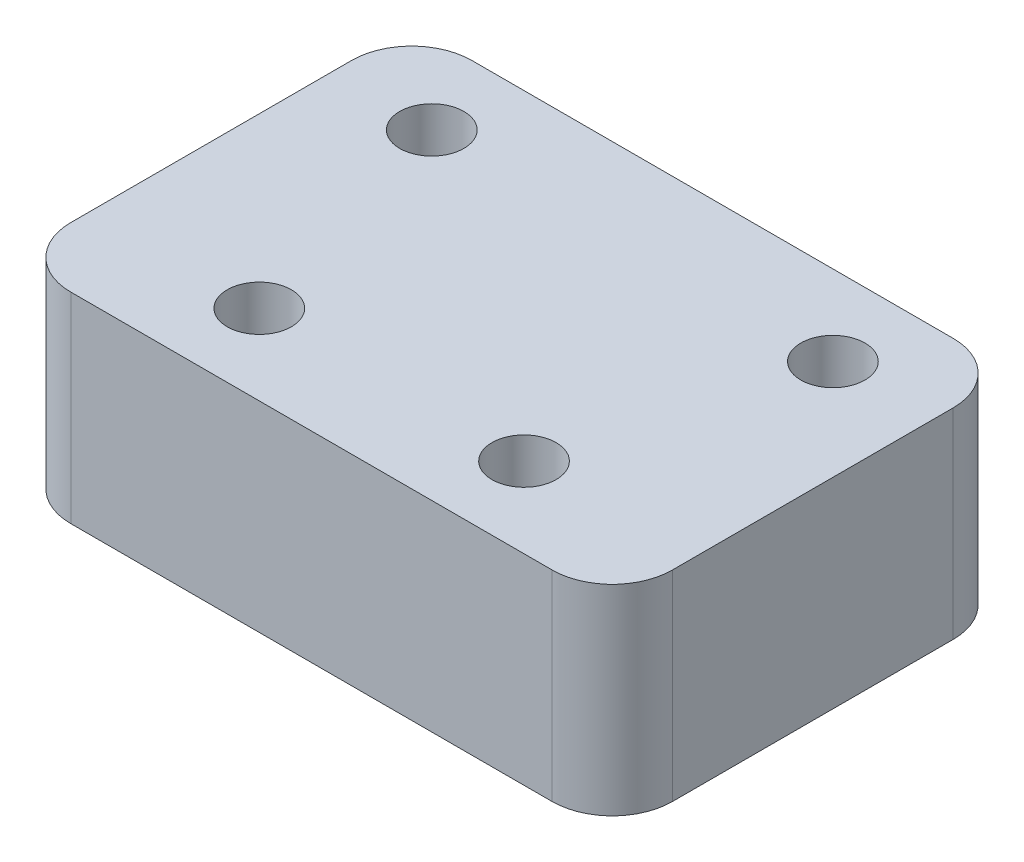
SolidWorks part; units mm, degrees
ref_plane "Front Plane" through (0, 0, 0) normal (0, 0, 1) x (1, 0, 0)
ref_plane "Top Plane" through (0, 0, 0) normal (0, 1, 0) x (1, 0, 0)
ref_plane "Right Plane" through (0, 0, 0) normal (1, 0, 0) x (0, 0, -1)
sketch "Sketch2" plane through (0, 0, 0) normal (0, 1, 0) x (1, 0, 0)
  line L0 (5, 16) -> (25, 16) construction
  line L1 (0, 0) -> (30, 0)
  line L2 (0, 0) -> (0, 20)
  line L3 (0, 20) -> (30, 20)
  line L4 (30, 0) -> (30, 20)
  line L5 (8.4, 4) -> (21.6, 4) construction
  circle A0 centre (5, 16) radius 1.6
  circle A1 centre (25, 16) radius 1.6
  circle A2 centre (8.4, 4) radius 1.6
  circle A3 centre (21.6, 4) radius 1.6
  dimension "D3" = 3.2
  dimension "D4" = 3.2
  dimension "D8" = 3.2
  dimension "D9" = 3.2
  dimension "D11" = 8.4
  dimension "D12" = 4
  dimension "D1" = 30
  dimension "D2" = 20
  dimension "D5" = 4
  dimension "D6" = 20
  dimension "D7" = 5
  dimension "D10" = 13.2
extrude "Boss-Extrude1" add sketch "Sketch2" along normal blind 10
fillet "Fillet1" radius 3 4 edges at (30, 5, -20) (30, 5, 0) (0, 5, 0) (0, 5, -20)
